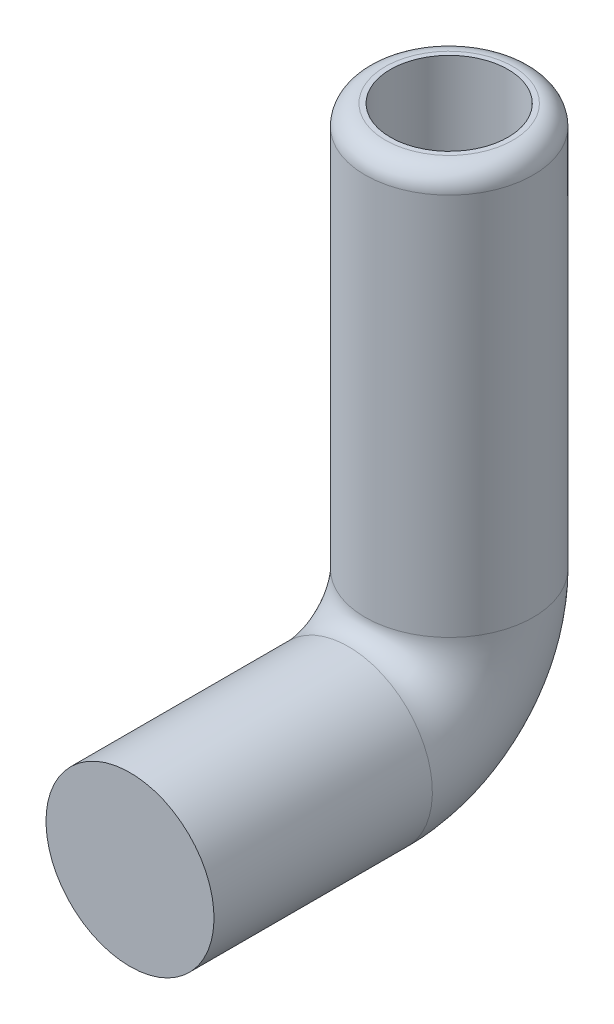
SolidWorks part; units mm, degrees
ref_plane "Front Plane" through (0, 0, 0) normal (0, 0, 1) x (1, 0, 0)
ref_plane "Top Plane" through (0, 0, 0) normal (0, 1, 0) x (1, 0, 0)
ref_plane "Right Plane" through (0, 0, 0) normal (1, 0, 0) x (0, 0, -1)
sketch "Sketch2" plane through (0, 0, 0) normal (1, 0, 0) x (0, 0, -1)
  line L0 (-65, 0) -> (0, 0)
  line L2 (30, 30) -> (30, 120)
  arc A0 (0, 0) -> (30, 30) centre (0, 30) ccw
  dimension "D1" = 30
  dimension "D2" = 90
  dimension "D3" = 65
sweep "Sweep1" add path "Sketch2" circular profile diameter 50 parameters "D3"=50
sketch "Sketch32" plane through (0, 120, 0) normal (0, 1, 0) x (1, 0, 0)
  circle A0 centre (0, 30) radius 25
  circle A1 centre (0, 30) radius 25 construction
  circle A2 centre (0, 30) radius 17.5
  circle M3 centre (0, 30) radius 25
  dimension "D1" = 35
extrude "Boss-Extrude2" add sketch "Sketch32" along normal blind 30 contours A2 M3 | A0
fillet "Fillet1" radius 6 1 edges at (0, 150, -5)
sketch "Sketch33" plane through (0, 120, 0) normal (0, 1, 0) x (1, 0, 0)
  circle A0 centre (0, 30) radius 17.5
  circle A1 centre (0, 30) radius 17.5 construction
extrude "Cut-Extrude1" cut sketch "Sketch33" against normal blind 80
